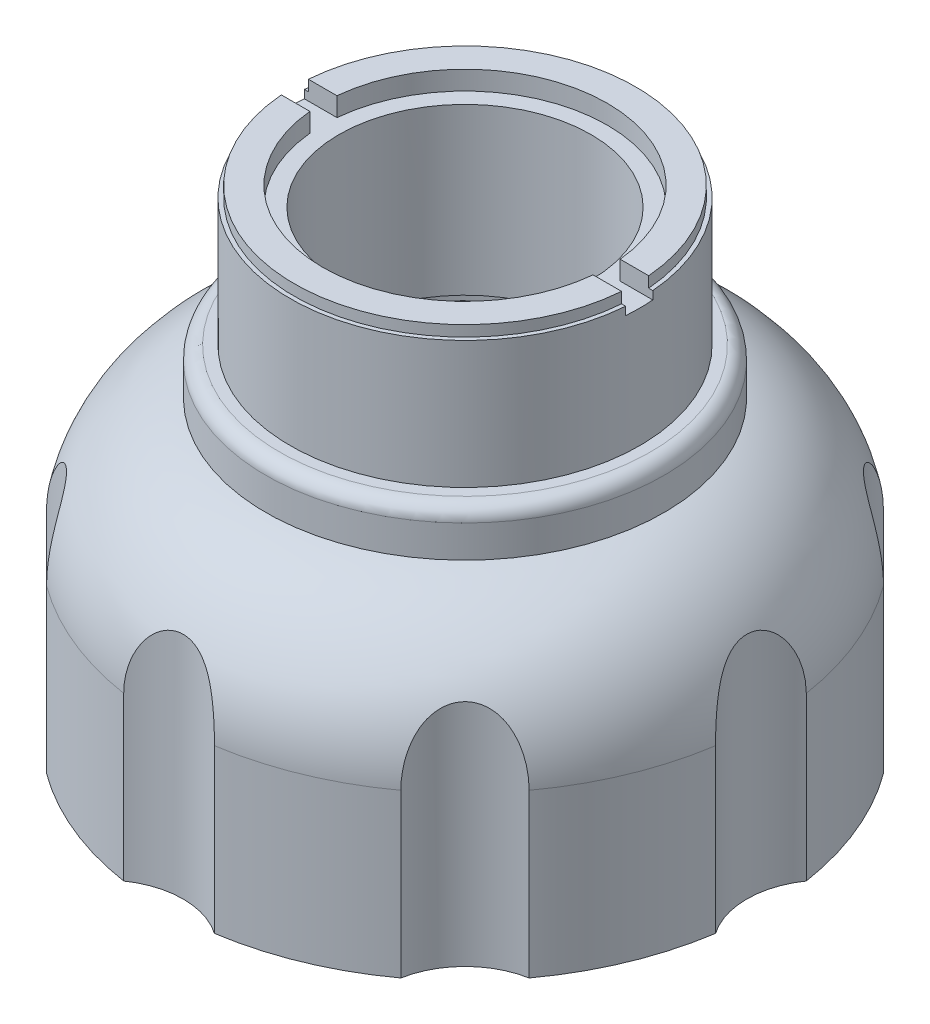
SolidWorks part; units mm, degrees
ref_plane "Front Plane" through (0, 0, 0) normal (0, 0, 1) x (1, 0, 0)
ref_plane "Top Plane" through (0, 0, 0) normal (0, 1, 0) x (1, 0, 0)
ref_plane "Right Plane" through (0, 0, 0) normal (1, 0, 0) x (0, 0, -1)
sketch "Croquis1" plane through (0, 0, 0) normal (0, 1, 0) x (1, 0, 0)
  circle A0 centre (0, 0) radius 11.05
  dimension "D1" = 22.1
extrude "Saliente-Extruir2" add sketch "Croquis1" along normal blind 6
sketch "Croquis3" plane through (0, 6, 0) normal (0, 1, 0) x (1, 0, 0)
  circle A3 centre (0, 0) radius 9.7
  circle A4 centre (0, 0) radius 9.7
  dimension "D1" = 1.35
extrude "Cortar-Extruir2" cut sketch "Croquis3" against normal blind 6
sketch "Croquis4" plane through (0, 0, 0) normal (0, 0, 1) x (1, 0, 0)
  line L2 (11.05, 6) -> (-11.05, 6) construction
  line L3 (0, 0) -> (0, 13.2709) construction
  line L5 (-11.05, 0) -> (11.05, 0) construction
  line L6 (-6.05, 9.65) -> (6.05, 9.65) construction
  line L8 (6.05, 9.65) -> (6.05, 11)
  line L9 (9.7, 6) -> (11.05, 6)
  arc A0 (11.05, 6) -> (6.05, 11) centre (6.05, 6) ccw
  arc A1 (9.7, 6) -> (6.05, 9.65) centre (6.05, 6) ccw
  circle A2 centre (6.05, 6) radius 3.65 construction
  circle A3 centre (6.05, 6) radius 5 construction
  point P15 (0, 9.65)
  dimension "D1" = 12.1
  dimension "D5" = 1.35
revolve "Revolución1" add sketch "Croquis4" angle 360 about L3
sketch "Croquis7" plane through (0, 0, 0) normal (0, -1, 0) x (1, 0, 0)
  line L0 (-9.4377, 9.4377) -> (0, 0) construction
  line L1 (0, 0) -> (0, 13.3469) construction
  line L2 (0, 0) -> (9.4377, 9.4377) construction
  line L3 (0, 0) -> (13.3469, 0) construction
  line L4 (0, 0) -> (9.4377, -9.4377) construction
  line L5 (0, 0) -> (0, -13.3469) construction
  line L6 (-8.9076, 6.5388) -> (-6.5388, 8.9076) construction
  line L7 (0, 0) -> (-13.3469, 0) construction
  line L8 (0, 0) -> (-9.4377, -9.4377) construction
  circle A0 centre (0, 0) radius 11.05 construction
  circle A1 centre (0, 0) radius 9.7 construction
  circle A3 centre (0, 13.3469) radius 2.9469
  circle A11 centre (-9.4377, 9.4377) radius 2.9469
  circle A12 centre (9.4377, 9.4377) radius 2.9469
  circle A13 centre (13.3469, 0) radius 2.9469
  circle A14 centre (9.4377, -9.4377) radius 2.9469
  circle A15 centre (0, -13.3469) radius 2.9469
  circle A16 centre (-9.4377, -9.4377) radius 2.9469
  circle A17 centre (-13.3469, 0) radius 2.9469
  point P16 (-7.3539, 7.3539)
  point P17 (-6.8589, 6.8589)
  dimension "D13" = 5.8939
  dimension "D14" = 5.8939
  dimension "D15" = 5.8939
  dimension "D16" = 5.8939
  dimension "D10" = 5.8939
  dimension "D11" = 5.8939
  dimension "D12" = 5.8939
  dimension "D1" = 13.3469
  dimension "D2" = 13.3469
  dimension "D3" = 3.35
  dimension "D4" = 0.7
  dimension "D5" = 13.3469
  dimension "D6" = 13.3469
  dimension "D7" = 13.3469
  dimension "D8" = 13.3469
  dimension "D9" = 13.3469
extrude "Cortar-Extruir3" cut sketch "Croquis7" against normal blind 10.56
sketch "Croquis8" plane through (0, 0, 0) normal (0, 0, 1) x (1, 0, 0)
  line L0 (-7.35, 10.8159) -> (-7.35, 12.5159)
  line L1 (-7.35, 10.8159) -> (-4.65, 10.8159)
  line L2 (0, 0) -> (0, 17.1321) construction
  line L3 (-1.675, 0) -> (1.675, 0) construction
  line L4 (-4.65, 10.8159) -> (-4.65, 12.5159)
  line L5 (-7.35, 12.5159) -> (-4.65, 12.5159)
  line L7 (6.05, 11) -> (-6.05, 11) construction
  dimension "D1" = 1.7
  dimension "D2" = 0.1841
  dimension "D3" = 4.65
  dimension "D4" = 7.35
revolve "Revolución2" add sketch "Croquis8" angle 360 about L2
fillet "Redondeo1" radius 0.5 1 edges at (0, 12.5159, -7.35)
sketch "Croquis9" plane through (0, 0, 0) normal (0, 0, 1) x (1, 0, 0)
  line L0 (-4.65, 12.5159) -> (-4.65, 17.6159)
  line L1 (6.85, 12.5159) -> (-6.85, 12.5159) construction
  line L2 (4.65, 12.5159) -> (-4.65, 12.5159) construction
  line L3 (-4.65, 17.6159) -> (-6.45, 17.6159)
  line L4 (-6.45, 17.6159) -> (-6.45, 12.5159)
  line L5 (-6.45, 12.5159) -> (-4.65, 12.5159)
  line L6 (0, 0) -> (0, 24.5342) construction
  line L7 (-1.675, 0) -> (1.675, 0) construction
  dimension "D1" = 1.8
  dimension "D2" = 5.1
  dimension "D3" = 4.65
revolve "Revolución3" add sketch "Croquis9" angle 360 about L6
sketch "Croquis14" plane through (0, 17.6159, 0) normal (0, 1, 0) x (1, 0, 0)
  circle A2 centre (0, 0) radius 6.45 construction
  circle A4 centre (0, 0) radius 6.3
  circle A5 centre (0, 0) radius 6.3
  circle A6 centre (0, 0) radius 6.45
  dimension "D1" = 0.15
extrude "Cortar-Extruir7" cut sketch "Croquis14" against normal blind 0.4
sketch "Croquis10" plane through (0, 17.6159, 0) normal (0, 1, 0) x (1, 0, 0)
  line L0 (-6.45, 0) -> (-5.3, 0) construction
  line L1 (-6.45, -0.5) -> (-5.2261, -0.5)
  line L2 (-6.45, 0.5) -> (-5.2261, 0.5)
  line L3 (-6.45, 0.5) -> (-6.45, -0.5)
  line L4 (6.45, 0.5) -> (6.45, -0.5)
  line L5 (5.2261, 0.5) -> (6.45, 0.5)
  line L6 (-6.45, 0.5) -> (6.45, 0.5) construction
  line L7 (5.3, 0) -> (6.45, 0) construction
  line L8 (-6.45, 0) -> (6.45, 0) construction
  line L9 (5.2261, -0.5) -> (6.45, -0.5)
  line L10 (-6.45, -0.5) -> (6.45, -0.5) construction
  circle A2 centre (0, 0) radius 6.45 construction
  circle A3 centre (0, 0) radius 5.25
  circle A5 centre (0, 0) radius 6.45 construction
  arc A9 (5.2261, 0.5) -> (-5.2261, 0.5) centre (0, 0) ccw
  arc A10 (-5.2261, -0.5) -> (5.2261, -0.5) centre (0, 0) ccw
  dimension "D1" = 1.05
  dimension "D2" = 0.5
  dimension "D3" = 0.5
extrude "Cortar-Extruir8" cut sketch "Croquis10" against normal blind 0.7
